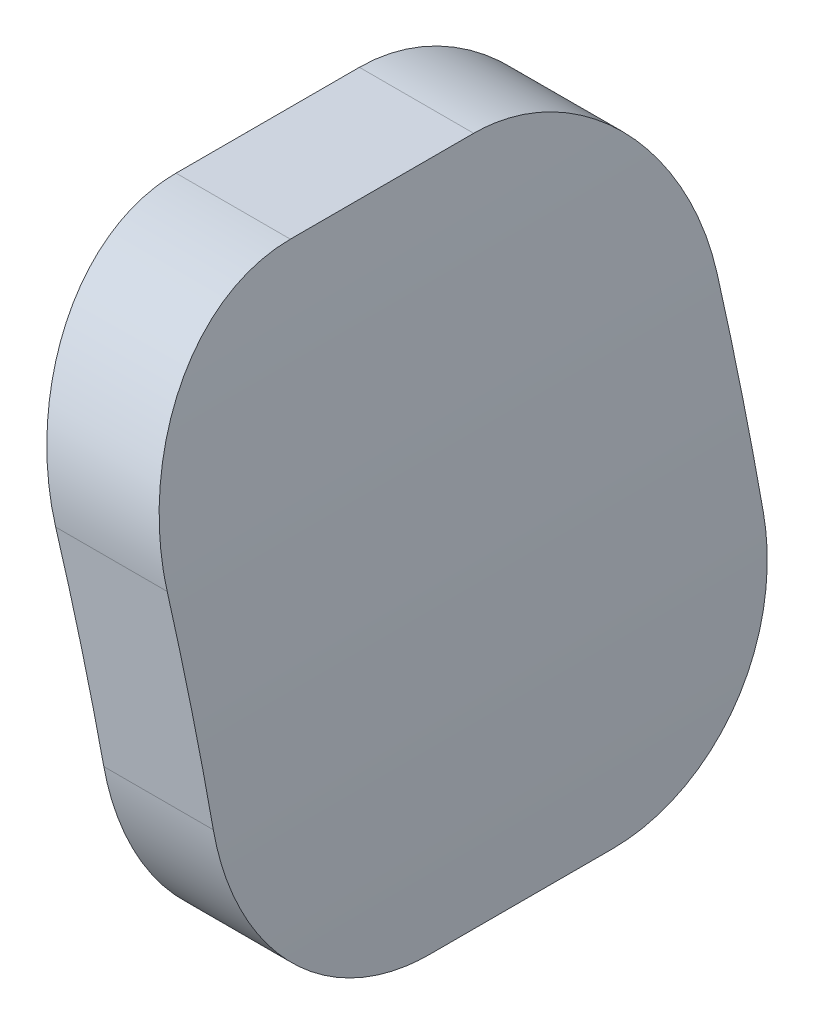
SolidWorks part; units mm, degrees
ref_plane "Front Plane" through (0, 0, 0) normal (0, 0, 1) x (1, 0, 0)
ref_plane "Top Plane" through (0, 0, 0) normal (0, 1, 0) x (1, 0, 0)
ref_plane "Right Plane" through (0, 0, 0) normal (1, 0, 0) x (0, 0, -1)
sketch "Sketch1" plane through (0, 0, 0) normal (0, 0, 1) x (1, 0, 0)
  line L0 (-2063.2072, -609.6) -> (2063.2072, -609.6) construction
  line L1 (-2087.4164, -520.7) -> (2087.4164, -520.7) construction
  line L2 (1818.7163, 1308.1) -> (1818.7163, -520.7) construction
  line L3 (1818.7163, -520.7) -> (2178.9277, -520.7) construction
  line L4 (1708.0136, 1308.1) -> (1818.7163, 1308.1)
  line L5 (2087.4164, -520.7) -> (2178.9277, -520.7)
  line L6 (1708.0136, 1308.1) -> (1708.0136, -520.7) construction
  circle A0 centre (0, 0) radius 2240.28 construction
  circle A1 centre (0, 0) radius 2151.38 construction
  arc A2 (2178.9277, -520.7) -> (1818.7163, 1308.1) centre (0, 0) ccw
  arc A3 (2087.4164, -520.7) -> (1708.0136, 1308.1) centre (0, 0) ccw
  point P6 (0, -2151.38)
  dimension "D1" = 4480.56
  dimension "D2" = 88.9
  dimension "D5" = 1828.8
  dimension "D7" = 1828.8
  dimension "D3" = 1541.78
  dimension "D4" = 88.9
  dimension "D6" = 0
extrude "Boss-Extrude2" add sketch "Sketch1" along normal blind 1066.8
sketch "Sketch2" plane through (0, 0, 0) normal (1, 0, 0) x (0, 0, -1)
  line L0 (-1066.8, 1308.1) -> (0, 1308.1) construction
  line L1 (-609.6, 317.5) -> (-457.2, 317.5)
  line L2 (-762, 469.9) -> (-762, 622.3)
  line L3 (-609.6, 774.7) -> (-457.2, 774.7)
  line L4 (-304.8, 469.9) -> (-304.8, 622.3)
  line L5 (-762, 317.5) -> (-304.8, 774.7) construction
  line L6 (-762, 774.7) -> (-304.8, 317.5) construction
  line L8 (-6736.08, -5778.5) -> (5669.28, -5778.5)
  line L9 (-6858, -5656.58) -> (-6858, 6748.78)
  line L10 (-6736.08, 6870.7) -> (5669.28, 6870.7)
  line L11 (5791.2, -5656.58) -> (5791.2, 6748.78)
  line L12 (-6858, -5778.5) -> (5791.2, 6870.7) construction
  line L13 (-6858, 6870.7) -> (5791.2, -5778.5) construction
  arc A0 (-609.6, 774.7) -> (-762, 622.3) centre (-609.6, 622.3) ccw
  arc A1 (-762, 469.9) -> (-609.6, 317.5) centre (-609.6, 469.9) ccw
  arc A2 (-304.8, 469.9) -> (-457.2, 317.5) centre (-457.2, 469.9) cw
  arc A3 (-304.8, 622.3) -> (-457.2, 774.7) centre (-457.2, 622.3) ccw
  arc A4 (5669.28, 6870.7) -> (5791.2, 6748.78) centre (5669.28, 6748.78) cw
  arc A5 (5791.2, -5656.58) -> (5669.28, -5778.5) centre (5669.28, -5656.58) cw
  arc A6 (-6858, -5656.58) -> (-6736.08, -5778.5) centre (-6736.08, -5656.58) ccw
  arc A7 (-6858, 6748.78) -> (-6736.08, 6870.7) centre (-6736.08, 6748.78) cw
  point P0 (-533.4, 546.1)
  point P8 (-533.4, 1308.1)
  point P23 (-533.4, 546.1)
  dimension "D2" = 152.4
  dimension "D3" = 121.92
  dimension "D1" = 762
  dimension "D4" = 457.2
  dimension "D5" = 457.2
  dimension "D6" = 6096
extrude "Cut-Extrude1" cut sketch "Sketch2" against normal through all both and the other way through all
